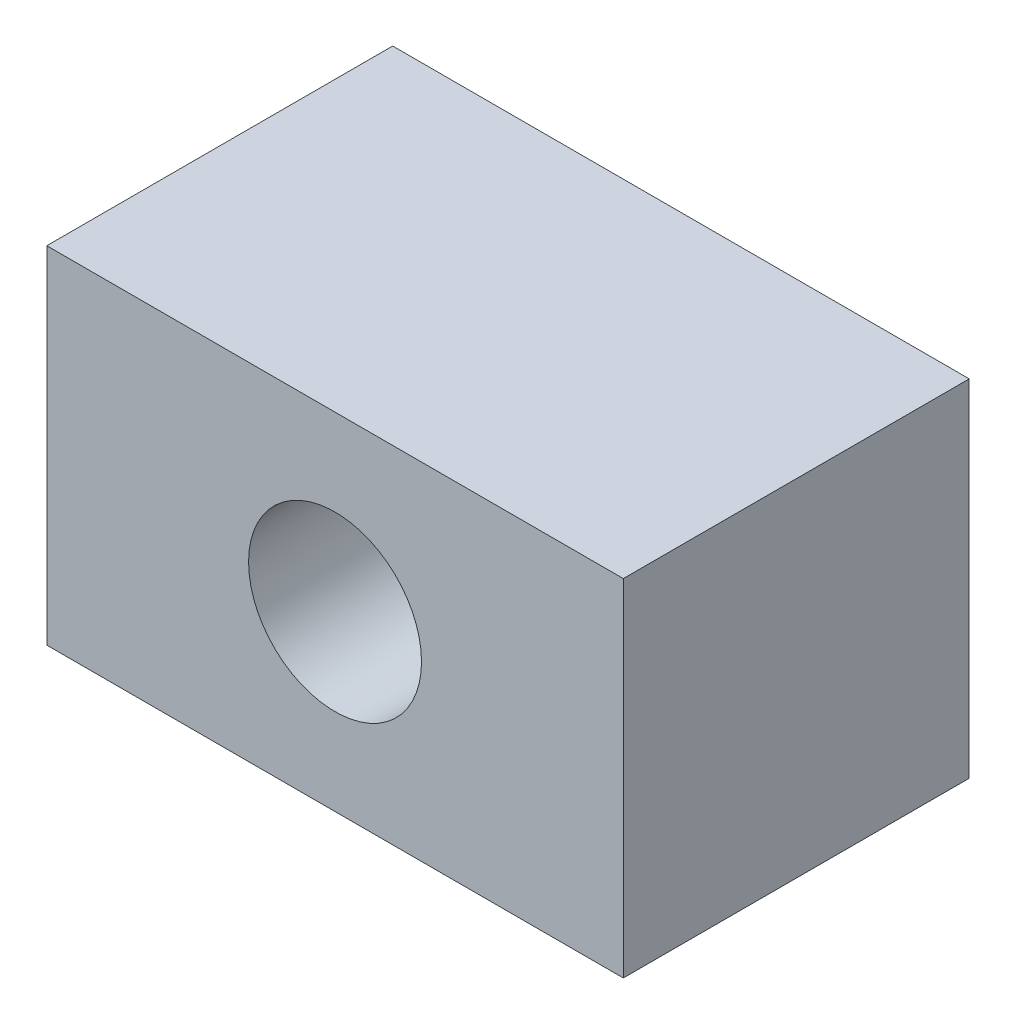
SolidWorks part; units mm, degrees
ref_plane "Front Plane" through (0, 0, 0) normal (0, 0, 1) x (1, 0, 0)
ref_plane "Top Plane" through (0, 0, 0) normal (0, 1, 0) x (1, 0, 0)
ref_plane "Right Plane" through (0, 0, 0) normal (1, 0, 0) x (0, 0, -1)
sketch "Sketch1" plane through (0, 0, 0) normal (1, 0, 0) x (0, 0, -1)
  line L1 (-15, -15) -> (15, -15)
  line L2 (-15, -15) -> (-15, 15)
  line L3 (-15, 15) -> (15, 15)
  line L4 (15, -15) -> (15, 15)
  line L5 (-15, -15) -> (15, 15) construction
  line L6 (-15, 15) -> (15, -15) construction
  point P0 (0, 0)
  dimension "D1" = 30
  dimension "D2" = 30
extrude "Boss-Extrude1" add sketch "Sketch1" along normal blind 50
sketch "Sketch2" plane through (0, 0, 15) normal (0, 0, 1) x (1, 0, 0)
  line L0 (50, -15) -> (0, -15) construction
  circle A0 centre (25, 0) radius 7.5
  dimension "D2" = 15
  dimension "D1" = 25
  dimension "D3" = 15
extrude "Cut-Extrude1" cut sketch "Sketch2" against normal blind 50
